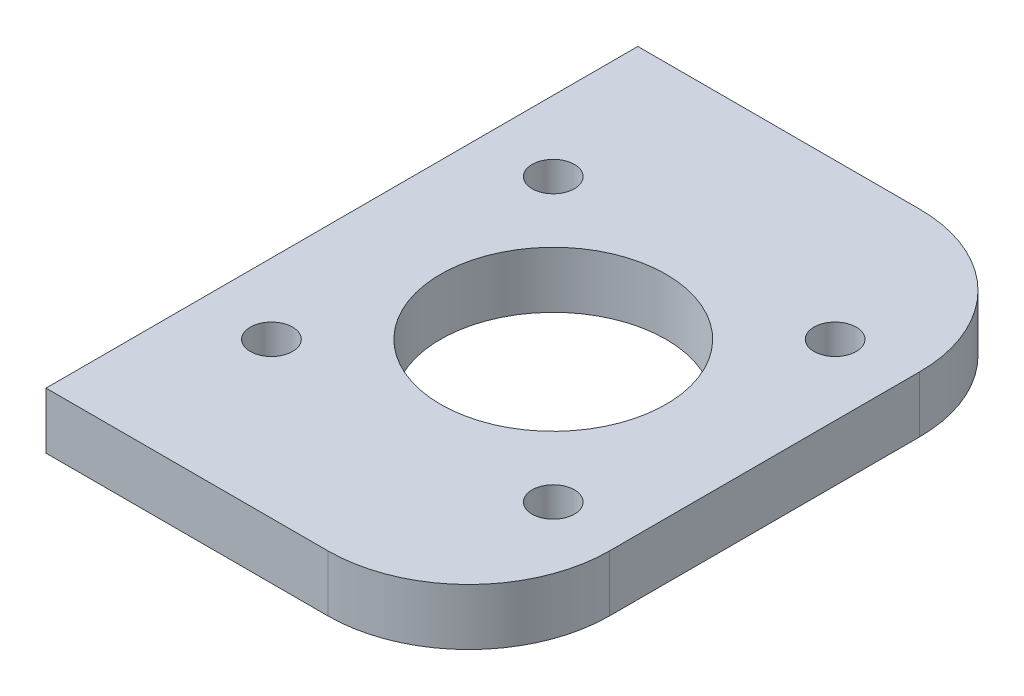
SolidWorks part; units mm, degrees
ref_plane "Front Plane" through (0, 0, 0) normal (0, 0, 1) x (1, 0, 0)
ref_plane "Top Plane" through (0, 0, 0) normal (0, 1, 0) x (1, 0, 0)
ref_plane "Right Plane" through (0, 0, 0) normal (1, 0, 0) x (0, 0, -1)
sketch "Sketch2" plane through (0, 0, 0) normal (0, 1, 0) x (1, 0, 0)
  line L1 (-15, 21) -> (15, 21)
  line L2 (-15, 21) -> (-15, -21)
  line L3 (-15, -21) -> (15, -21)
  line L4 (15, 21) -> (15, -21)
  line L5 (-15, 21) -> (15, -21) construction
  line L6 (-15, -21) -> (15, 21) construction
  circle A0 centre (0, 0) radius 8
  point P0 (0, 0)
  dimension "D3" = 16
  dimension "D1" = 42
  dimension "D2" = 30
extrude "Boss-Extrude1" add sketch "Sketch2" along normal blind 4
fillet "Fillet1" radius 10 2 edges at (15, 2, -21) (15, 2, 21)
sketch "Sketch3" plane through (0, 4, 0) normal (0, 1, 0) x (1, 0, 0)
  circle A0 centre (-10, 10) radius 1.5
  circle A1 centre (10, 10) radius 1.5
  circle A2 centre (10, -10) radius 1.5
  circle A3 centre (-10, -10) radius 1.5
  point P0 (0, 0)
  point P1 (0, 0)
  dimension "D3" = 3
  dimension "D1" = 20
  dimension "D2" = 20
extrude "Cut-Extrude1" cut sketch "Sketch3" against normal blind 6
